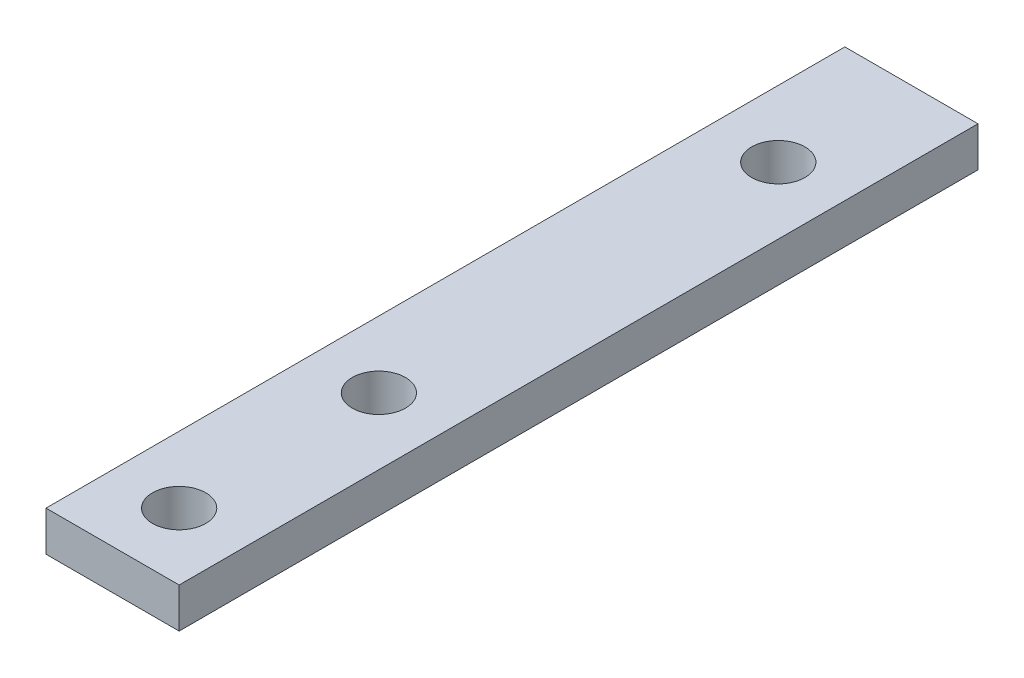
SolidWorks part; units mm, degrees
ref_plane "Front Plane" through (0, 0, 0) normal (0, 0, 1) x (1, 0, 0)
ref_plane "Top Plane" through (0, 0, 0) normal (0, 1, 0) x (1, 0, 0)
ref_plane "Right Plane" through (0, 0, 0) normal (1, 0, 0) x (0, 0, -1)
sketch "Sketch1" plane through (0, 0, 0) normal (0, 1, 0) x (1, 0, 0)
  line L0 (0, 0) -> (0, 60) construction
  line L1 (0, 0) -> (-5, 0)
  line L2 (-5, 0) -> (-5, 60)
  line L3 (-5, 60) -> (5, 60)
  line L4 (5, 60) -> (5, 0)
  line L5 (5, 0) -> (0, 0)
  circle A0 centre (0, 20) radius 2
  circle A1 centre (0, 5) radius 2
  circle A2 centre (0, 50) radius 2
  dimension "D1" = 4
  dimension "D2" = 10
  dimension "D3" = 15
  dimension "D4" = 5
  dimension "D5" = 10
  dimension "D6" = 30
extrude "Boss-Extrude1" add sketch "Sketch1" along normal blind 3
